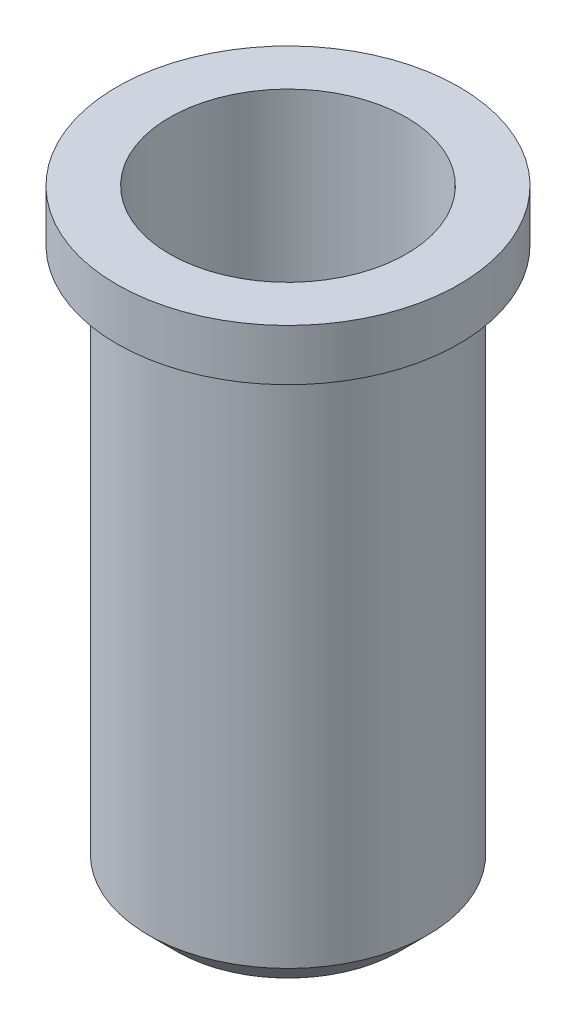
SolidWorks part; units mm, degrees
ref_plane "Front Plane" through (0, 0, 0) normal (0, 0, 1) x (1, 0, 0)
ref_plane "Top Plane" through (0, 0, 0) normal (0, 1, 0) x (1, 0, 0)
ref_plane "Right Plane" through (0, 0, 0) normal (1, 0, 0) x (0, 0, -1)
sketch "Sketch1" plane through (0, 0, 0) normal (0, 0, 1) x (1, 0, 0)
  line L0 (0, 0) -> (0, 8.4047) construction
  line L1 (0, 0) -> (0.9906, 0)
  line L2 (0, 0) -> (0, 0.254)
  line L4 (1.2446, 0.254) -> (1.2446, 4.953)
  line L8 (1.0541, 5.4102) -> (1.0541, 0.8382)
  line L9 (1.0541, 5.4102) -> (1.524, 5.4102)
  line L10 (1.0541, 5.4102) -> (1.0541, 7.9798)
  line L11 (1.2446, 4.953) -> (1.524, 4.953)
  line L12 (1.524, 5.4102) -> (1.524, 4.953)
  line L13 (1.2446, 0.254) -> (0.9906, 0)
  line L14 (1.0541, 0.8382) -> (0, 0.254)
  dimension "D1" = 0.4572
  dimension "D2" = 1.524
  dimension "D3" = 5.4102
  dimension "D4" = 1.2446
  dimension "D5" = 0.254
  dimension "D6" = 0.254
  dimension "D7" = 4.572
  dimension "D8" = 0.1905
  dimension "D9" = 0.254
revolve "Revolve1" add sketch "Sketch1" angle 360 about L0
